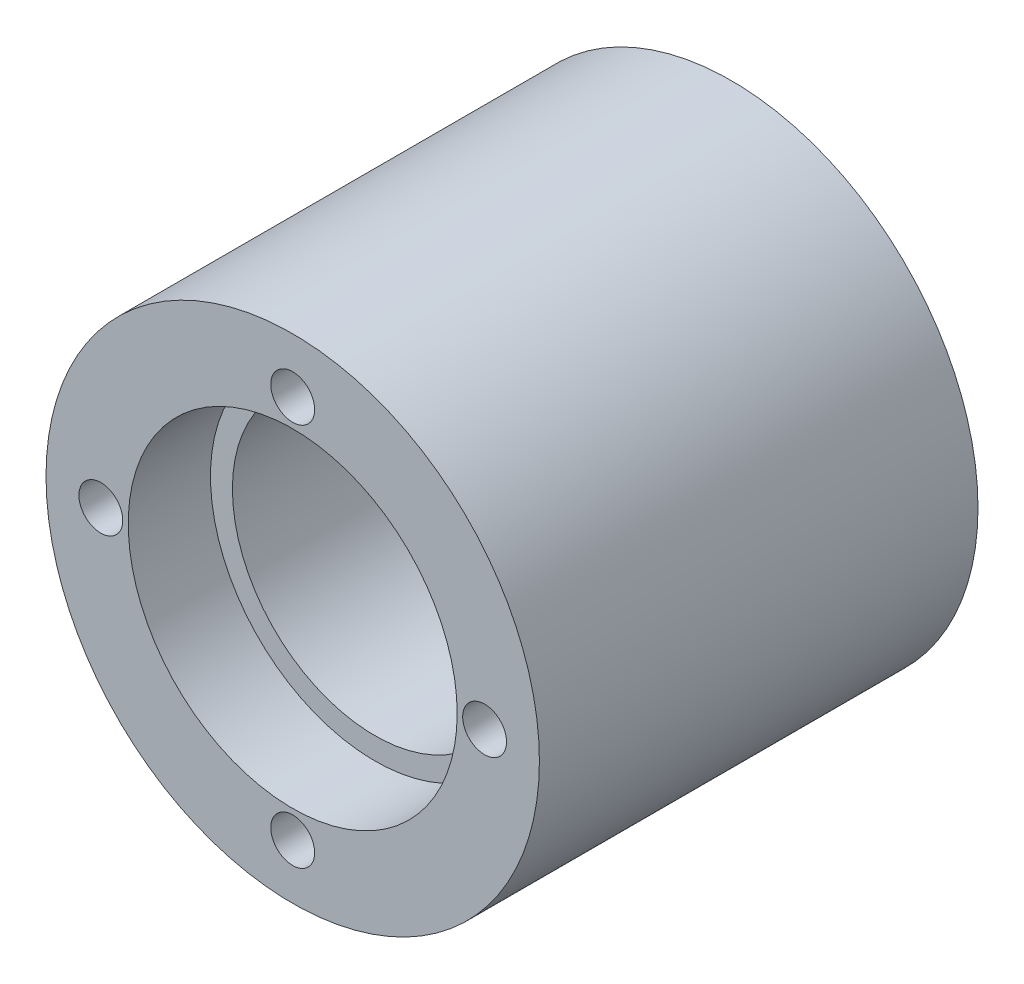
SolidWorks part; units mm, degrees
ref_plane "Front Plane" through (0, 0, 0) normal (0, 0, 1) x (1, 0, 0)
ref_plane "Top Plane" through (0, 0, 0) normal (0, 1, 0) x (1, 0, 0)
ref_plane "Right Plane" through (0, 0, 0) normal (1, 0, 0) x (0, 0, -1)
sketch "Sketch1" plane through (0, 0, 0) normal (0, 0, 1) x (1, 0, 0)
  circle A0 centre (0, 0) radius 22.5
  circle A1 centre (0, 0) radius 15
  circle A2 centre (0, 17.5) radius 2
  circle A3 centre (17.5, 0) radius 2
  circle A4 centre (0, -17.5) radius 2
  circle A5 centre (-17.5, 0) radius 2
  point P15 (0, 0)
  dimension "D1" = 30
  dimension "D2" = 4
  dimension "D4" = 45
  dimension "D3" = 17.5
  dimension "D5" = 4
extrude "Boss-Extrude1" add sketch "Sketch1" along normal mid plane 40
sketch "Sketch2" plane through (0, 0, 0) normal (0, 0, 1) x (1, 0, 0)
  circle A0 centre (0, 0) radius 13
  circle A1 centre (0, 0) radius 15 construction
  circle A2 centre (0, 0) radius 15
  dimension "D1" = 26
extrude "Boss-Extrude2" add sketch "Sketch2" along normal mid plane 25
